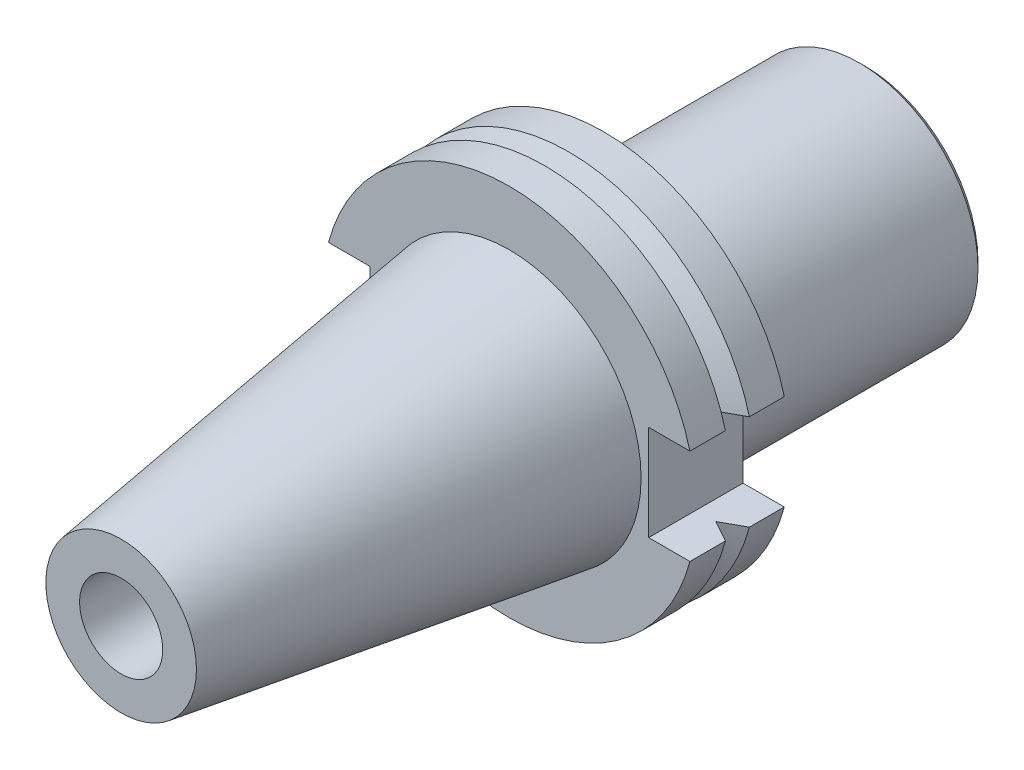
SolidWorks part; units mm, degrees
ref_plane "前视基准面" through (0, 0, 0) normal (0, 0, 1) x (1, 0, 0)
ref_plane "上视基准面" through (0, 0, 0) normal (0, 1, 0) x (1, 0, 0)
ref_plane "右视基准面" through (0, 0, 0) normal (1, 0, 0) x (0, 0, -1)
sketch "草图1" plane through (0, 0, 0) normal (0, 1, 0) x (1, 0, 0)
  line L0 (0, -65.4) -> (0, 60) construction
  line L1 (0, -65.4) -> (12.6875, -65.4)
  line L2 (12.6875, -65.4) -> (22.225, 0)
  line L3 (22.225, 0) -> (31.5, 0)
  line L4 (31.5, 0) -> (31.5, 15.9)
  line L5 (31.5, 15.9) -> (20, 15.9)
  line L6 (20, 15.9) -> (20, 59)
  line L7 (20, 59) -> (19, 60)
  line L8 (19, 60) -> (0, 60)
  line L9 (0, 60) -> (0, -65.4)
revolve "旋转1" add sketch "草图1" angle 360 about L0
sketch "草图2" plane through (0, 0, 0) normal (0, 1, 0) x (1, 0, 0)
  line L0 (0, 0) -> (0, -65.4) construction
  line L1 (28, 8) -> (32, 5.6906)
  line L2 (32, 5.6906) -> (32, 10.3094)
  line L3 (32, 10.3094) -> (28, 8)
revolve "切除-旋转1" cut sketch "草图2" angle 360 about L0
sketch "草图3" plane through (0, 0, 0) normal (0, 0, 1) x (1, 0, 0)
  line L0 (23.5, -8.05) -> (33, -8.05)
  line L1 (33, -8.05) -> (33, 8.05)
  line L2 (33, 8.05) -> (23.5, 8.05)
  line L3 (23.5, 8.05) -> (23.5, -8.05)
  line L4 (-33, -8.05) -> (-23.5, -8.05)
  line L5 (-23.5, -8.05) -> (-23.5, 8.05)
  line L6 (-23.5, 8.05) -> (-33, 8.05)
  line L7 (-33, 8.05) -> (-33, -8.05)
extrude "切除-拉伸1" cut sketch "草图3" against normal through all
ref_plane "基准面1" through (0, 0, -15.9) normal (0, 0, 1) x (1, 0, 0)
sketch "草图4" plane through (0, 0, -15.9) normal (0, 0, 1) x (1, 0, 0)
  circle A0 centre (0, 25) radius 4
extrude "切除-拉伸2" cut sketch "草图4" along normal blind 6
ref_plane "基准面2" through (0, 0, -60) normal (0, 0, 1) x (1, 0, 0)
sketch "草图5" plane through (0, 0, -60) normal (0, 0, 1) x (1, 0, 0)
  circle A0 centre (0, 0) radius 10
extrude "切除-拉伸3" cut sketch "草图5" along normal blind 50
ref_plane "基准面3" through (0, 0, 65.4) normal (0, 0, 1) x (1, 0, 0)
sketch "草图6" plane through (0, 0, 65.4) normal (0, 0, 1) x (1, 0, 0)
  circle A0 centre (0, 0) radius 7
extrude "切除-拉伸4" cut sketch "草图6" against normal blind 30
ref_plane "基准面4" through (0, 0, -10) normal (0, 0, 1) x (1, 0, 0)
sketch "草图7" plane through (0, 0, -10) normal (0, 0, 1) x (1, 0, 0)
  circle A0 centre (0, 0) radius 3
extrude "切除-拉伸5" cut sketch "草图7" along normal blind 45.4
